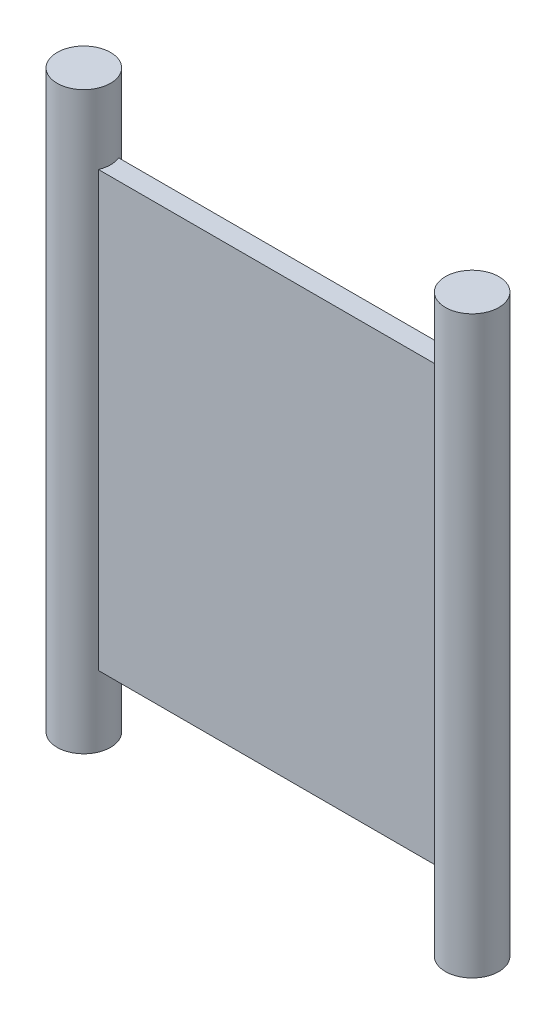
SolidWorks part; units mm, degrees
ref_plane "Front Plane" through (0, 0, 0) normal (0, 0, 1) x (1, 0, 0)
ref_plane "Top Plane" through (0, 0, 0) normal (0, 1, 0) x (1, 0, 0)
ref_plane "Right Plane" through (0, 0, 0) normal (1, 0, 0) x (0, 0, -1)
sketch "Sketch1" plane through (0, 0, 0) normal (0, 1, 0) x (1, 0, 0)
  line L1 (9.62, 0.5) -> (-9.62, 0.5)
  line L2 (9.62, 0.5) -> (9.62, -0.5)
  line L3 (9.62, -0.5) -> (-9.62, -0.5)
  line L4 (-9.62, 0.5) -> (-9.62, -0.5)
  line L5 (9.62, 0.5) -> (-9.62, -0.5) construction
  line L6 (9.62, -0.5) -> (-9.62, 0.5) construction
  point P0 (0, 0)
  dimension "D1" = 19.24
  dimension "D3" = 1
extrude "Boss-Extrude1" add sketch "Sketch1" along normal blind 21.5
ref_plane "Plane1" through (0, 10.75, 0) normal (0, 1, 0) x (1, 0, 0)
sketch "Sketch2" plane through (0, 10.75, 0) normal (0, 1, 0) x (1, 0, 0)
  line L0 (9.62, -0.5) -> (9.62, 0.5) construction
  line L1 (-9.62, 0.5) -> (-9.62, -0.5) construction
  line L2 (9.62, -0.5) -> (9.62, 0.5) construction
  line L3 (-9.62, 0.5) -> (-9.62, -0.5) construction
  circle A0 centre (-9.62, 0) radius 1.325
  circle A1 centre (9.62, 0) radius 1.325
  dimension "D1" = 2.65
extrude "Boss-Extrude2" add sketch "Sketch2" along normal mid plane 28.5
